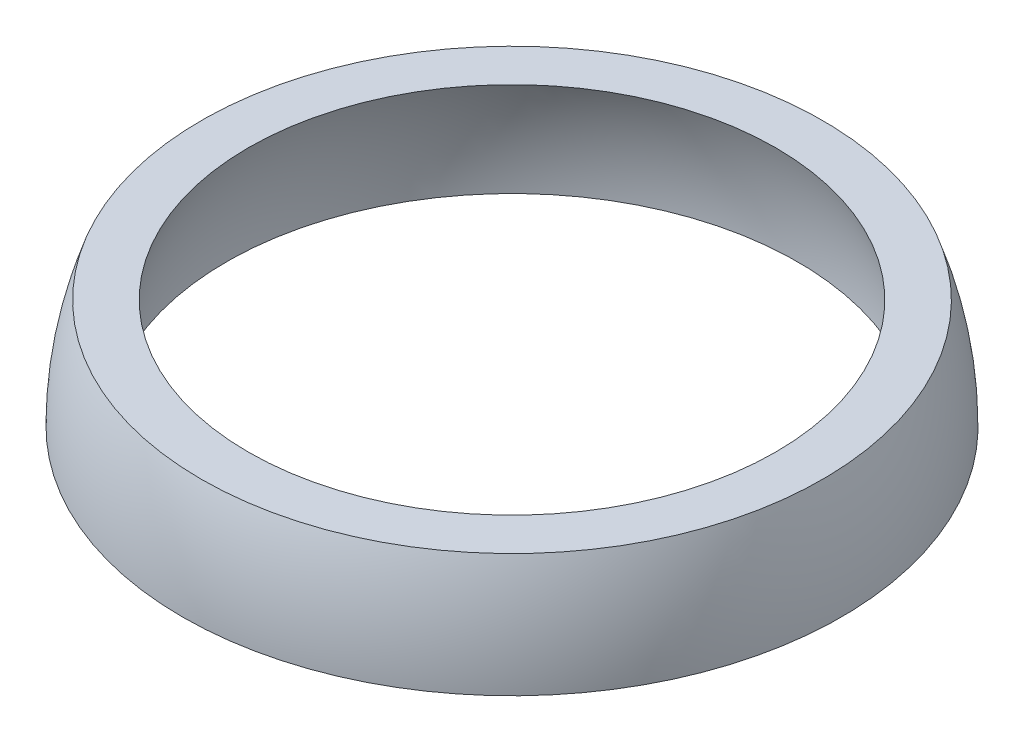
SolidWorks part; units mm, degrees
ref_plane "Front Plane" through (0, 0, 0) normal (0, 0, 1) x (1, 0, 0)
ref_plane "Top Plane" through (0, 0, 0) normal (0, 1, 0) x (1, 0, 0)
ref_plane "Right Plane" through (0, 0, 0) normal (1, 0, 0) x (0, 0, -1)
sketch "Sketch1" plane through (0, 0, 0) normal (0, 0, 1) x (1, 0, 0)
  line L0 (0, 19.05) -> (0, -19.05) construction
  line L1 (-19.05, 0) -> (19.05, 0) construction
  line L2 (16.51, 0) -> (19.05, 0)
  line L5 (0, 0) -> (0, 6.35) construction
  line L6 (15.24, 6.35) -> (17.9605, 6.35)
  line L7 (0, 6.35) -> (17.9605, 6.35) construction
  arc A5 (19.05, 0) -> (17.9605, 6.35) centre (0, 0) ccw
  arc A6 (16.51, 0) -> (15.24, 6.35) centre (0, 0) ccw
  dimension "D3" = 6.35
  dimension "D2" = 2.54
revolve "Revolve2" add sketch "Sketch1" angle 360 about L0
